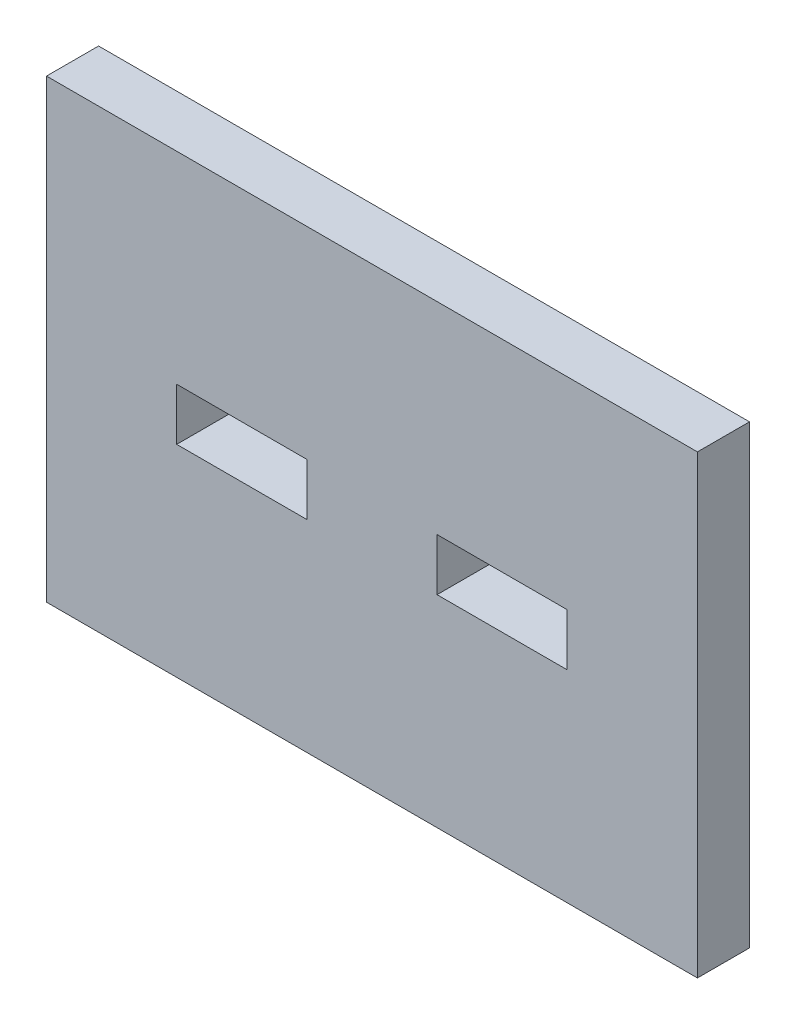
SolidWorks part; units mm, degrees
ref_plane "Front Plane" through (0, 0, 0) normal (0, 0, 1) x (1, 0, 0)
ref_plane "Top Plane" through (0, 0, 0) normal (0, 1, 0) x (1, 0, 0)
ref_plane "Right Plane" through (0, 0, 0) normal (1, 0, 0) x (0, 0, -1)
sketch "Sketch1" plane through (0, 0, 0) normal (0, 0, 1) x (1, 0, 0)
  line L1 (0, 0) -> (50, 0)
  line L2 (0, 0) -> (0, 35)
  line L3 (0, 35) -> (50, 35)
  line L4 (50, 0) -> (50, 35)
  dimension "D1" = 50
  dimension "D2" = 35
extrude "Boss-Extrude1" add sketch "Sketch1" along normal blind 4
sketch "Sketch2" plane through (0, 0, 4) normal (0, 0, 1) x (1, 0, 0)
  line L0 (0, 17.5) -> (50, 17.5) construction
  line L1 (0, 35) -> (0, 0) construction
  line L2 (50, 0) -> (50, 35) construction
  line L4 (10, 19.5) -> (20, 19.5)
  line L5 (10, 19.5) -> (10, 15.5)
  line L6 (10, 15.5) -> (20, 15.5)
  line L7 (20, 19.5) -> (20, 15.5)
  line L8 (10, 19.5) -> (20, 15.5) construction
  line L9 (10, 15.5) -> (20, 19.5) construction
  line L10 (30, 19.5) -> (40, 19.5)
  line L11 (30, 19.5) -> (30, 15.5)
  line L12 (30, 15.5) -> (40, 15.5)
  line L13 (40, 19.5) -> (40, 15.5)
  line L14 (30, 19.5) -> (40, 15.5) construction
  line L15 (30, 15.5) -> (40, 19.5) construction
  point P6 (15, 17.5)
  point P11 (35, 17.5)
  dimension "D1" = 10
  dimension "D2" = 10
  dimension "D3" = 10
  dimension "D4" = 10
  dimension "D5" = 4
  dimension "D6" = 4
extrude "Cut-Extrude1" cut sketch "Sketch2" against normal blind 4
